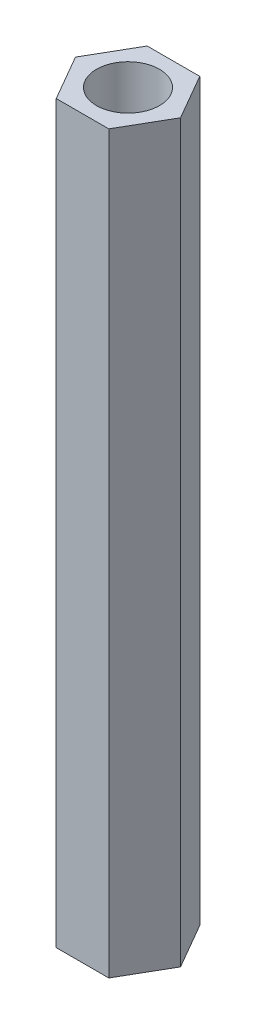
SolidWorks part; units mm, degrees
ref_plane "Plano frontal" through (0, 0, 0) normal (0, 0, 1) x (1, 0, 0)
ref_plane "Plano superior" through (0, 0, 0) normal (0, 1, 0) x (1, 0, 0)
ref_plane "Plano direito" through (0, 0, 0) normal (1, 0, 0) x (0, 0, -1)
sketch "Esboço1" plane through (0, 0, 0) normal (0, 1, 0) x (1, 0, 0)
  line L1 (2.5, 0) -> (1.25, 2.1651)
  line L2 (1.25, 2.1651) -> (-1.25, 2.1651)
  line L3 (-1.25, 2.1651) -> (-2.5, 0)
  line L4 (-2.5, 0) -> (-1.25, -2.1651)
  line L5 (-1.25, -2.1651) -> (1.25, -2.1651)
  line L6 (1.25, -2.1651) -> (2.5, 0)
  circle A0 centre (0, 0) radius 2.1651 construction
  dimension "D1" = 5
extrude "Ressalto-extrusão1" add sketch "Esboço1" along normal blind 35
sketch "Esboço2" plane through (0, 35, 0) normal (0, 1, 0) x (1, 0, 0)
  circle A0 centre (0, 0) radius 1.5
  dimension "D1" = 3
extrude "Corte-extrusão1" cut sketch "Esboço2" against normal blind 8
sketch "Esboço3" plane through (0, 0, 0) normal (0, -1, 0) x (1, 0, 0)
  circle A0 centre (0, 0) radius 1.5
  dimension "D1" = 3
extrude "Corte-extrusão2" cut sketch "Esboço3" against normal blind 8
